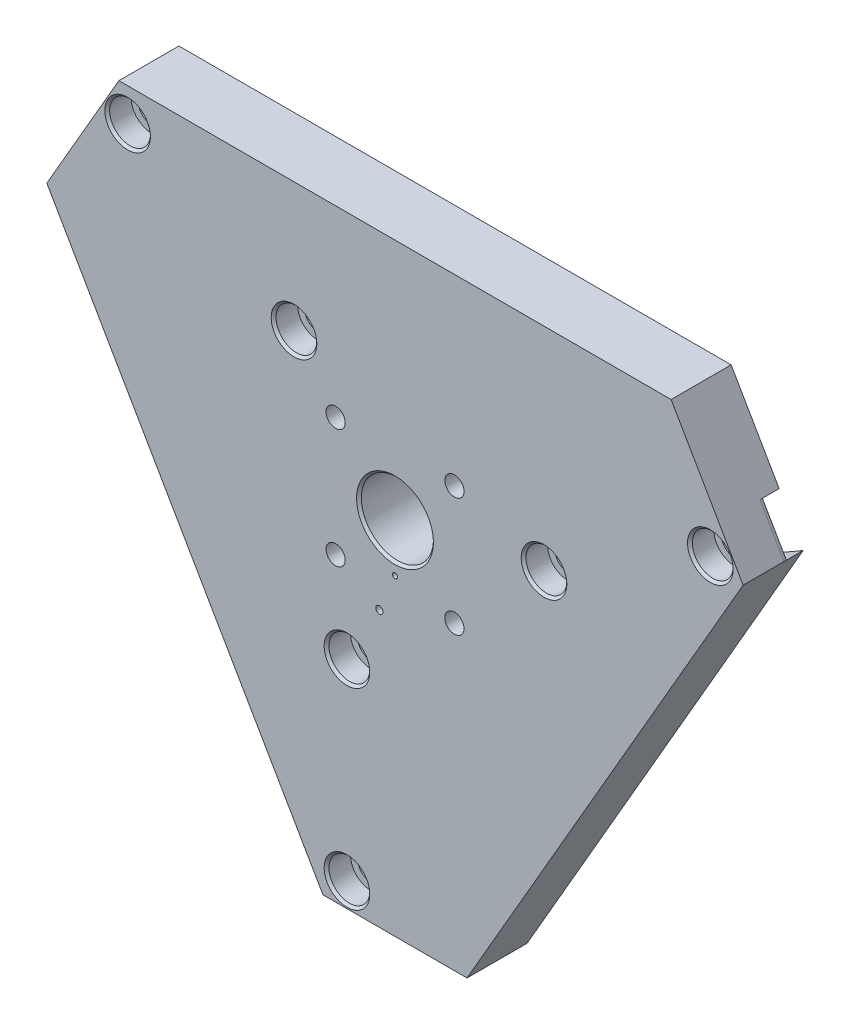
SolidWorks part; units mm, degrees
ref_plane "前视基准面" through (0, 0, 0) normal (0, 0, 1) x (1, 0, 0)
ref_plane "上视基准面" through (0, 0, 0) normal (0, 1, 0) x (1, 0, 0)
ref_plane "右视基准面" through (0, 0, 0) normal (1, 0, 0) x (0, 0, -1)
sketch "草图1" plane through (0, 0, 0) normal (0, 0, 1) x (1, 0, 0)
  line L0 (7.305, -868.0818) -> (7.305, 49131.9182) construction
  line L1 (7.305, 119.593) -> (213.5393, 238.6624) construction
  line L2 (7.305, 119.593) -> (-157.5391, 214.7658) construction
  line L4 (-107.695, 220.6292) -> (-137.695, 168.6677)
  line L5 (-22.695, -30.5181) -> (37.305, -30.5181)
  line L6 (152.305, 168.6677) -> (122.305, 220.6292)
  line L9 (152.305, 168.6677) -> (37.305, -30.5181)
  line L12 (-137.695, 168.6677) -> (-22.695, -30.5181)
  line L13 (-107.695, 220.6292) -> (122.305, 220.6292)
  circle A0 centre (7.305, 119.593) radius 15
  dimension "D12" = 30
  dimension "D2" = 60
  dimension "D3" = 60
  dimension "D4" = 60
  dimension "D5" = 230
  dimension "D6" = 230
  dimension "D7" = 230
  dimension "D8" = 120
  dimension "D9" = 120
  dimension "D10" = 115
  dimension "D11" = 115
extrude "拉伸1" add sketch "草图1" along normal blind 25
sketch "草图5" plane through (0, 0, 0) normal (0, 0, -1) x (-1, 0, 0)
  line L0 (-7.305, -866.5506) -> (-7.305, 49133.4494) construction
  line L1 (-7.305, 119.593) -> (160.353, 216.3904) construction
  line L2 (-7.305, 119.593) -> (-137.305, 194.6485) construction
  line L3 (26.7623, 150.8087) -> (130.6697, 210.7997)
  line L4 (-170.3624, 179.0932) -> (-61.3724, 116.1677)
  line L5 (125.1321, 230.6966) -> (16.7623, 168.1292)
  line L6 (16.7623, 168.1292) -> (26.7623, 150.8087)
  line L7 (-61.3724, 116.1677) -> (-51.3724, 133.4882)
  line L8 (-51.3724, 133.4882) -> (-160.3624, 196.4137)
  line L9 (-152.305, 168.6677) -> (-122.305, 220.6292) construction
  line L11 (2.695, 74.4819) -> (22.695, 74.4819)
  line L12 (22.695, 74.4819) -> (22.695, -45.5181)
  line L13 (22.695, -45.5181) -> (2.695, -45.5181)
  line L14 (2.695, -45.5181) -> (2.695, 74.4819)
  line L15 (-170.3624, 179.0932) -> (-160.3624, 196.4137)
  line L17 (22.695, -30.5181) -> (-37.305, -30.5181) construction
  line L18 (-152.305, 168.6677) -> (-122.305, 220.6292) construction
  line L19 (125.1321, 230.6966) -> (130.6697, 210.7997)
  line L20 (107.695, 220.6292) -> (137.695, 168.6677) construction
  dimension "D2" = 120
  dimension "D3" = 20
  dimension "D4" = 30
  dimension "D5" = 20
  dimension "D6" = 30
  dimension "D7" = 20
  dimension "D8" = 120
  dimension "D9" = 30
  dimension "D10" = 105
  dimension "D11" = 105
  dimension "D12" = 105
extrude "切除-拉伸1" cut sketch "草图5" against normal blind 6
fillet "圆角1" radius 5 1 edges at (-16.7623, 168.1292, 3)
fillet "圆角2" radius 5 1 edges at (-26.7623, 150.8087, 3)
fillet "圆角3" radius 5 1 edges at (61.3724, 116.1677, 3)
fillet "圆角4" radius 5 1 edges at (51.3724, 133.4882, 3)
fillet "圆角5" radius 5 1 edges at (-22.695, 74.4819, 3)
fillet "圆角6" radius 5 1 edges at (-2.695, 74.4819, 3)
sketch "草图7" plane through (0, 0, 0) normal (0, 0, -1) x (-1, 0, 0)
  line L0 (107.695, 220.6292) -> (137.695, 168.6677) construction
  line L1 (31.0924, 153.3087) -> (117.695, 203.3087) construction
  line L2 (-55.7025, 135.9882) -> (-142.305, 185.9882) construction
  line L3 (-152.305, 168.6677) -> (-122.305, 220.6292) construction
  line L4 (2.695, 69.4819) -> (2.695, -30.5181) construction
  line L5 (22.695, -30.5181) -> (-37.305, -30.5181) construction
  circle A0 centre (104.0347, 206.969) radius 5.5
  circle A1 centre (34.7527, 166.969) radius 5.5
  circle A2 centre (-138.6448, 172.328) radius 5.5
  circle A3 centre (-69.3627, 132.328) radius 5.5
  circle A4 centre (12.695, 59.4819) radius 5.5
  circle A5 centre (12.695, -20.5181) radius 5.5
  dimension "D1" = 11
  dimension "D2" = 10
  dimension "D3" = 10
  dimension "D4" = 10
  dimension "D5" = 10
  dimension "D6" = 10
  dimension "D7" = 10
  dimension "D8" = 90
  dimension "D9" = 90
  dimension "D10" = 10
  dimension "D11" = 10
  dimension "D12" = 10
  dimension "D13" = 90
extrude "切除-拉伸2" cut sketch "草图7" against normal through all
sketch "草图8" plane through (0, 0, 25) normal (0, 0, 1) x (1, 0, 0)
  circle A0 centre (-12.695, 59.4819) radius 8.5
  circle A1 centre (-12.695, -20.5181) radius 8.5
  circle A2 centre (69.3627, 132.328) radius 8.5
  circle A3 centre (138.6448, 172.328) radius 8.5
  circle A4 centre (-34.7527, 166.969) radius 8.5
  circle A5 centre (-104.0347, 206.969) radius 8.5
  dimension "D1" = 17
  dimension "D2" = 17
  dimension "D3" = 17
  dimension "D4" = 17
  dimension "D5" = 17
  dimension "D6" = 17
extrude "切除-拉伸3" cut sketch "草图8" against normal blind 10
hole_wizard "M8 螺纹孔1" positions "草图10" profile "草图9" tap size "M8" standard "ISO"
sketch "草图10" plane through (0, 0, 0) normal (0, 0, -1) x (-1, 0, 0)
  line L0 (-7.305, -880.407) -> (-7.305, 49119.593) construction
  line L1 (-1007.305, 119.593) -> (48992.695, 119.593) construction
  circle A0 centre (-7.305, 119.593) radius 35
  point P0 (-42.305, 119.593)
  point P1 (-7.305, 154.593)
  point P3 (27.695, 119.593)
  point P5 (-7.305, 84.593)
  dimension "D1" = 70
sketch "草图9" plane through (42.305, 119.593, 0) normal (1, 0, 0) x (0, 1, 0)
  line L0 (0, 0) -> (0, 11.7929)
  line L1 (0, 11.7929) -> (3.4, 9.75)
  line L2 (3.4, 9.75) -> (3.4, 6)
  line L3 (3.4, 6) -> (4, 6)
  line L4 (4, 6) -> (4, 0)
  line L5 (4, 0) -> (0, 0)
  line L10 (0, 11.7929) -> (-3.4, 9.75) construction
  line L11 (0, -6.35) -> (0, 107.95) construction
  dimension "蹟恇謂郰芛眻噤" = 6.8
  dimension "蹟恇謂郰芛旮僅" = 9.75
  dimension "蹟恇翋眻噤" = 8
  dimension "蹟恇旮僅" = 6
  dimension "絳芛褒僅" = 118
hole_wizard "M8 螺纹孔2" positions "草图12" profile "草图11" tap size "M8" standard "ISO"
sketch "草图12" plane through (0, 0, 25) normal (0, 0, 1) x (1, 0, 0)
  line L0 (-699.8017, -587.5138) -> (34655.5373, 34767.8252) construction
  line L1 (714.4118, -587.5138) -> (-34640.9272, 34767.8252) construction
  circle A0 centre (7.305, 119.593) radius 35
  point P0 (32.0538, 94.8442)
  point P1 (32.0538, 144.3417)
  point P3 (-17.4106, 144.3747)
  point P5 (-17.4106, 94.8112)
  dimension "D1" = 70
sketch "草图11" plane through (32.0538, 94.8442, 25) normal (1, 0, 0) x (0, -1, 0)
  line L0 (0, 0) -> (0, 11.7929)
  line L1 (0, 11.7929) -> (3.4, 9.75)
  line L2 (3.4, 9.75) -> (3.4, 6)
  line L3 (3.4, 6) -> (4, 6)
  line L4 (4, 6) -> (4, 0)
  line L5 (4, 0) -> (0, 0)
  line L10 (0, 11.7929) -> (-3.4, 9.75) construction
  line L11 (0, -6.35) -> (0, 107.95) construction
  dimension "蹟恇謂郰芛眻噤" = 6.8
  dimension "蹟恇謂郰芛旮僅" = 9.75
  dimension "蹟恇翋眻噤" = 8
  dimension "蹟恇旮僅" = 6
  dimension "絳芛褒僅" = 118
fillet "圆角7" radius 2 3 edges at (-12.695, -30.5181, 6) (147.305, 177.328, 6) (-112.695, 211.969, 6)
chamfer "倒角1" distance 2 angle 45 1 edges at (22.305, 119.593, 0)
chamfer "倒角2" distance 1 angle 45 1 edges at (-95.5347, 206.969, 25)
chamfer "倒角3" distance 1 angle 45 6 edges at (22.305, 119.593, 25) (147.1448, 172.328, 25) (77.8627, 132.328, 25) (-4.195, -20.5181, 25) (-4.195, 59.4819, 25) (-26.2527, 166.969, 25)
sketch "草图13" plane through (0, 0, 25) normal (0, 0, 1) x (1, 0, 0)
  line L0 (7.305, -896.407) -> (7.305, 49103.593) construction
  line L1 (-998.649, 83.993) -> (49001.351, 83.993) construction
  line L2 (-1056.7474, 99.593) -> (48943.2526, 99.593) construction
  line L3 (0.805, -912.663) -> (0.805, 49087.337) construction
  circle A1 centre (7.305, 119.593) radius 20 construction
  dimension "D1" = 40
  dimension "D2" = 15.6
  dimension "D3" = 20
  dimension "D4" = 6.5
hole_wizard "M3 螺纹孔1" positions "3D草图1" profile "草图14" tap size "M3" standard "ISO"
sketch3d "3D草图1"
  line L0 (0.805, -912.663, 25) -> (0.805, 49087.337, 25) construction
  line L1 (-998.649, 83.993, 25) -> (49001.351, 83.993, 25) construction
  point P0 (0.805, 83.993, 25)
sketch "草图14" plane through (0.805, 83.993, 25) normal (1, 0, 0) x (0, -1, 0)
  line L0 (0, 0) -> (0, 8.2511)
  line L1 (0, 8.2511) -> (1.25, 7.5)
  line L2 (1.25, 7.5) -> (1.25, 6)
  line L3 (1.25, 6) -> (1.5, 6)
  line L4 (1.5, 6) -> (1.5, 0)
  line L5 (1.5, 0) -> (0, 0)
  line L10 (0, 8.2511) -> (-1.25, 7.5) construction
  line L11 (0, -6.35) -> (0, 107.95) construction
  dimension "蹟恇謂郰芛眻噤" = 2.5
  dimension "蹟恇謂郰芛旮僅" = 7.5
  dimension "蹟恇翋眻噤" = 3
  dimension "蹟恇旮僅" = 6
  dimension "絳芛褒僅" = 118
sketch "草图15" plane through (0, 0, 25) normal (0, 0, 1) x (1, 0, 0)
  line L0 (7.305, -200896.407) -> (7.305, 249103.593) construction
  line L1 (-201056.7474, 99.593) -> (248943.2526, 99.593) construction
  circle A0 centre (7.305, 99.593) radius 1.05
  dimension "D1" = 2.1
extrude "切除-拉伸4" cut sketch "草图15" against normal blind 10
